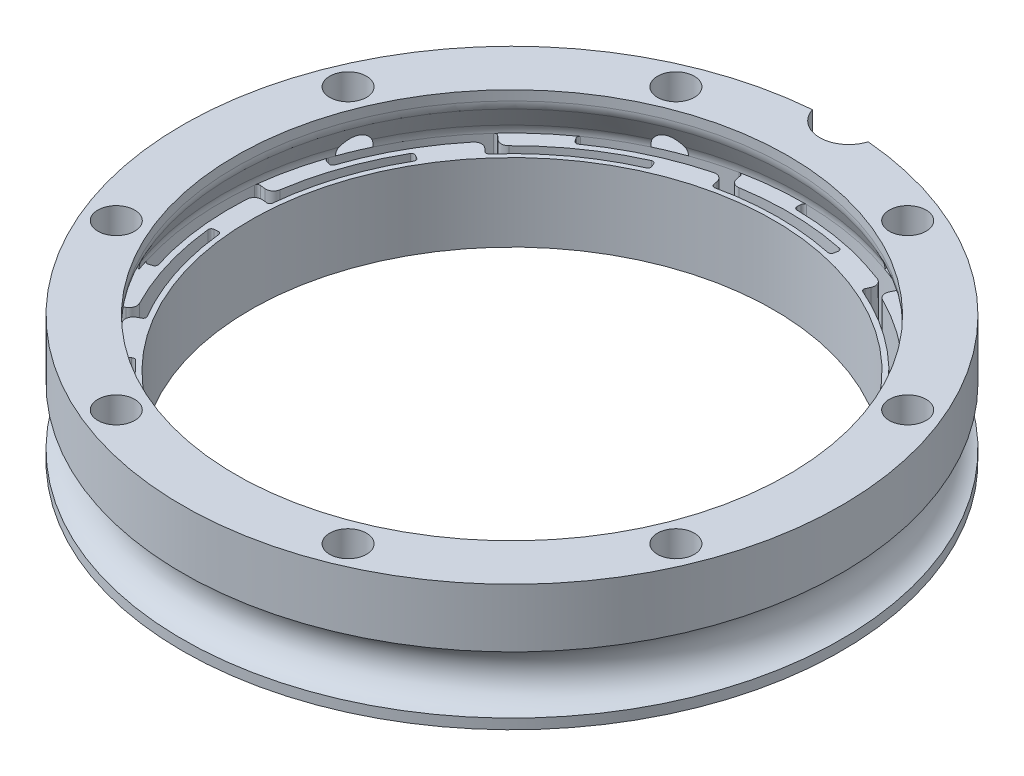
SolidWorks part; units mm, degrees
ref_plane "Front Plane" through (0, 0, 0) normal (0, 0, 1) x (1, 0, 0)
ref_plane "Top Plane" through (0, 0, 0) normal (0, 1, 0) x (1, 0, 0)
ref_plane "Right Plane" through (0, 0, 0) normal (1, 0, 0) x (0, 0, -1)
sketch "Sketch1" plane through (0, 0, 0) normal (0, 1, 0) x (1, 0, 0)
  circle A0 centre (0, 0) radius 34
  circle A1 centre (0, 0) radius 27
  dimension "D1" = 68
  dimension "D2" = 54
extrude "Boss-Extrude1" add sketch "Sketch1" along normal mid plane 8
sketch "Sketch3" plane through (0, 4, 0) normal (0, 1, 0) x (1, 0, 0)
  line L0 (12.7208, 27.2799) -> (12.0446, 25.8298)
  line L1 (11.3846, 26.7806) -> (10.708, 25.3296)
  line L2 (0, 30.1) -> (0, 29.1)
  line L3 (21.3504, 18.8789) -> (20.6012, 18.2165)
  arc A0 (0, 30.1) -> (12.7208, 27.2799) centre (0, 0) cw
  arc A1 (12.0446, 25.8298) -> (21.3504, 18.8789) centre (0, 0) cw
  arc A2 (0, 29.1) -> (11.3846, 26.7806) centre (0, 0) cw
  arc A3 (10.708, 25.3296) -> (20.6012, 18.2165) centre (0, 0) cw
  circle A4 centre (0, 0) radius 27 construction
  dimension "D2" = 0.5
  dimension "D3" = 25
  dimension "D4" = 1.6
  dimension "D1" = 1
extrude "Cut-Extrude2" cut sketch "Sketch3" against normal through all
fillet "Fillet1" radius 0.3 6 edges at (0, 0, -29.1) (0, 0, -30.1) (20.6012, 0, -18.2165) (21.3504, 0, -18.8789) (10.708, 0, -25.3296) (12.7208, 0, -27.2799)
fillet "Fillet2" radius 0.8 2 edges at (12.0446, 0, -25.8298) (11.3846, 0, -26.7806)
pattern_circular "CirPattern1" count 10 over 360 about axis through (0, 0, 0) along (0, 1, 0) of "Cut-Extrude2", "Fillet1", "Fillet2"
sketch "Sketch5" [suppressed] plane through (0, 0, 0) normal (1, 0, 0) x (0, 0, -1)
  line L0 (-30.5, 4) -> (-30.5, 12.2)
  line L1 (-30.5, 12.2) -> (-5.7397, 12.2)
  line L2 (-5.7397, 12.2) -> (-5.7397, 20.0385)
  line L3 (-5.7397, 20.0385) -> (0, 20.0385)
  line L4 (0, 20.0385) -> (0, 8.2)
  line L5 (0, 8.2) -> (-23.5, 8.2)
  line L10 (-30.5, 4) -> (-27.7, 4)
  line L11 (-27.7, 4) -> (-23.5, 8.2)
  line L12 (-25, 4) -> (-23.5, 8.2) construction
  dimension "D1" = 45
  dimension "D2" = 4
  dimension "D3" = 1.5
revolve "Revolve1" [suppressed] add sketch "Sketch5" angle 360 about L4
sketch "Sketch6" plane through (0, 0, 0) normal (0, 0, 1) x (1, 0, 0)
  line L1 (0, 0) -> (0, -16.6169) construction
  line L2 (-34, 0) -> (-34.75, 0) construction
  line L3 (-34, 4) -> (-34, -4) construction
  circle A0 centre (-34.75, 0) radius 3.05
  dimension "D1" = 6.1
  dimension "D2" = 0.75
revolve "Cut-Revolve1" cut sketch "Sketch6" angle 360 about L1
sketch "Sketch12" plane through (0, 4, 0) normal (0, 1, 0) x (1, 0, 0)
  circle A0 centre (0, 0) radius 30.1 construction
  arc A1 (-29.9111, 3.3673) -> (-28.719, -9.0128) centre (0, 0) ccw construction
sketch "Sketch10" plane through (0, 0, 0) normal (0, 0, 1) x (1, 0, 0)
  line L0 (-34, 9) -> (-34, 4)
  line L1 (-34, 4) -> (-30.1, 4)
  line L3 (-28.5, 9) -> (-34, 9)
  line L5 (-28.719, 4) -> (-30.1, 4) construction
  line L6 (-29.8881, 4.8678) -> (-28.7119, 7.1322)
  line L7 (0, 0) -> (0, 6.0244) construction
  line L8 (-28.5, 9) -> (-28.5, 8)
  arc A0 (-30.1, 4) -> (-29.8881, 4.8678) centre (-28.2173, 4) cw
  arc A2 (-28.5, 8) -> (-28.7119, 7.1322) centre (-30.3827, 8) cw
  dimension "D1" = 5.5
  dimension "D3" = 5
  dimension "D4" = 1
revolve "Revolve2" add sketch "Sketch10" angle 360 about L7
sketch "Sketch7" plane through (0, 4, 0) normal (0, 1, 0) x (1, 0, 0)
  circle A0 centre (0, 34.75) radius 3
  circle A1 centre (0, 0) radius 34 construction
  dimension "D1" = 0.75
  dimension "D2" = 6
extrude "Cut-Extrude3" cut sketch "Sketch7" along normal up to surface (5 mm away) and the other way up to surface up to face at (0, 9, -34) other way up to plane "Top Plane"
sketch "Sketch8" plane through (0, 4, 0) normal (0, 1, 0) x (1, 0, 0)
  circle A0 centre (0, 0) radius 27.5
  arc A1 (-23.8403, 13.7073) -> (-27.3708, 2.6631) centre (0, 0) ccw construction
  circle A2 centre (0, 0) radius 15
  dimension "D1" = 30
extrude "Boss-Extrude2" [suppressed] add sketch "Sketch8" along normal blind 5
sketch "Sketch11" plane through (0, 9, 0) normal (0, 1, 0) x (1, 0, 0)
  line L0 (10.9065, 26.3306) -> (13.0112, 31.4119) construction
  line L1 (0, 0) -> (15.0619, 0) construction
  circle A0 centre (0, 0) radius 28.5 construction
  arc A1 (-2.8707, 33.8786) -> (2.8707, 33.8786) centre (0, 0) ccw construction
  circle A2 centre (11.9589, 28.8712) radius 1.9
  circle A3 centre (28.8712, 11.9589) radius 1.9
  circle A4 centre (28.8712, -11.9589) radius 1.9
  circle A5 centre (11.9589, -28.8712) radius 1.9
  circle A6 centre (-11.9589, -28.8712) radius 1.9
  circle A7 centre (-28.8712, -11.9589) radius 1.9
  circle A8 centre (-28.8712, 11.9589) radius 1.9
  circle A9 centre (-11.9589, 28.8712) radius 1.9
  circle A10 centre (0, 0) radius 31.25 construction
  dimension "D2" = 3.8
  dimension "D1" = 67.5
  dimension "D3" = 8
extrude "Cut-Extrude4" cut sketch "Sketch11" against normal up to surface (5 mm away) up to face at (0, 4, 27)
